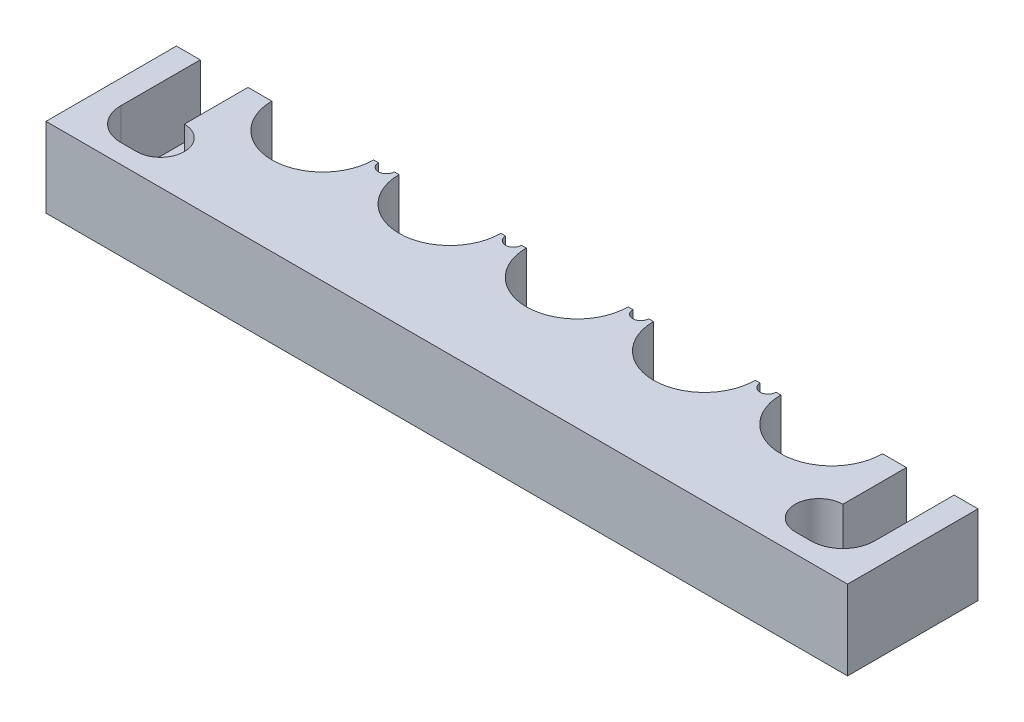
SolidWorks part; units mm, degrees
ref_plane "Plano frontal" through (0, 0, 0) normal (0, 0, 1) x (1, 0, 0)
ref_plane "Plano superior" through (0, 0, 0) normal (0, 1, 0) x (1, 0, 0)
ref_plane "Plano direito" through (0, 0, 0) normal (1, 0, 0) x (0, 0, -1)
sketch "Esboço1" plane through (0, 0, 0) normal (0, 1, 0) x (1, 0, 0)
  line L0 (-25.2, 0) -> (-19.2, 0)
  line L5 (25.2, 0) -> (25.2, -8.2)
  line L6 (25.2, -8.2) -> (-25.2, -8.2)
  line L7 (-25.2, -8.2) -> (-25.2, 0)
  line L8 (-12.8, 0) -> (-11.2, 0)
  line L9 (-4.8, 0) -> (-3.2, 0)
  line L10 (3.2, 0) -> (4.8, 0)
  line L11 (11.2, 0) -> (12.8, 0)
  line L12 (19.2, 0) -> (25.2, 0)
  arc A0 (-19.2, 0) -> (-12.8, 0) centre (-16, 0) ccw
  arc A1 (-11.2, 0) -> (-4.8, 0) centre (-8, 0) ccw
  arc A2 (-3.2, 0) -> (3.2, 0) centre (0, 0) ccw
  arc A3 (4.8, 0) -> (11.2, 0) centre (8, 0) ccw
  arc A4 (12.8, 0) -> (19.2, 0) centre (16, 0) ccw
  dimension "D1" = 6.4
  dimension "D4" = 6
  dimension "D5" = 5
  dimension "D3" = 8
  dimension "D2" = 5
extrude "Ressalto-extrusão1" add sketch "Esboço1" along normal mid plane 5
sketch "Esboço2" plane through (0, 2.5, 0) normal (0, 1, 0) x (1, 0, 0)
  line L0 (-11.2, 0) -> (-12.8, 0) construction
  line L1 (12.8, 0) -> (11.2, 0) construction
  circle A0 centre (-12, 0) radius 0.5
  circle A1 centre (-4, 0) radius 0.5
  circle A2 centre (4, 0) radius 0.5
  circle A3 centre (12, 0) radius 0.5
  point P13 (12, 0)
  dimension "D1" = 1
  dimension "D2" = 4
extrude "Corte-extrusão1" cut sketch "Esboço2" against normal through all
sketch "Esboço3" plane through (0, 2.5, 0) normal (0, 1, 0) x (1, 0, 0)
  line L0 (-19.2, 0) -> (-25.2, 0) construction
  line L2 (-23.7, 0) -> (-20.7, 0)
  line L3 (-23.7, 0) -> (-23.7, -5)
  line L4 (-21.7, -7) -> (-20.7, -7)
  line L5 (-20.7, 0) -> (-20.7, -4)
  line L6 (0, -2.75) -> (0, 2.75) construction
  line L7 (20.7, 0) -> (20.7, -4)
  line L8 (21.7, -7) -> (20.7, -7)
  line L9 (23.7, 0) -> (23.7, -5)
  line L10 (23.7, 0) -> (20.7, 0)
  arc A0 (-20.7, -7) -> (-20.7, -4) centre (-20.7, -5.5) ccw
  arc A1 (20.7, -7) -> (20.7, -4) centre (20.7, -5.5) cw
  arc A2 (21.7, -7) -> (23.7, -5) centre (21.7, -5) ccw
  arc A3 (-23.7, -5) -> (-21.7, -7) centre (-21.7, -5) ccw
  point P10 (23.7, -7)
  point P14 (-23.7, -7)
  point P16 (-22.2, 0)
  point P17 (-22.2, 0)
  dimension "D2" = 3
  dimension "D4" = 2
  dimension "D1" = 3
  dimension "D3" = 7
extrude "Corte-extrusão2" cut sketch "Esboço3" against normal blind 4
